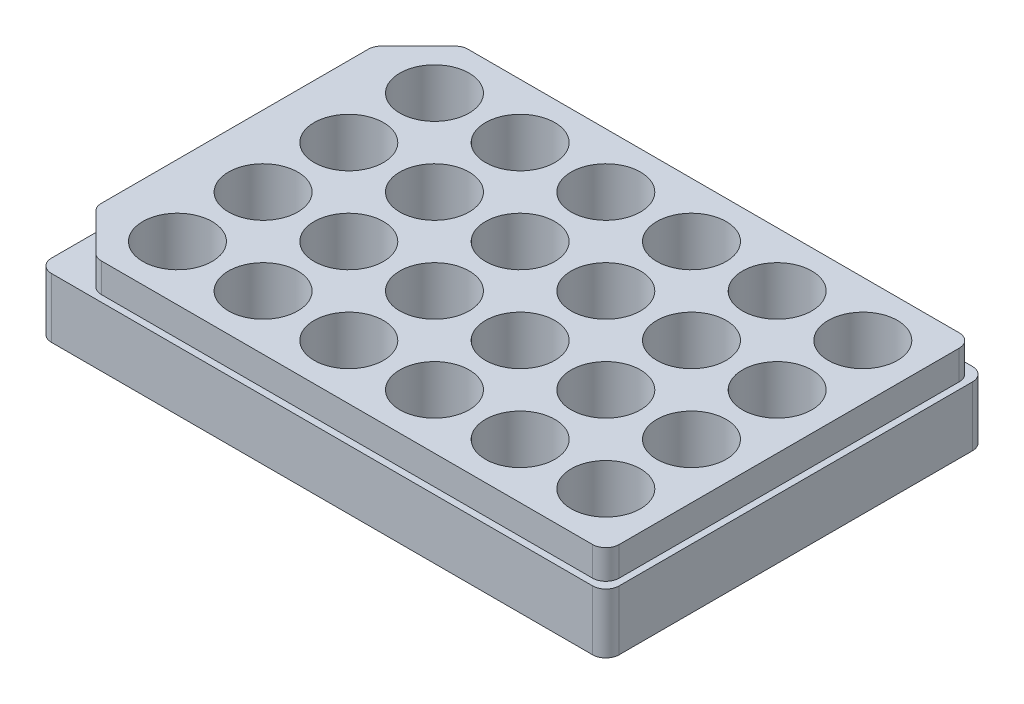
SolidWorks part; units mm, degrees
material "Acrylic (Medium-high impact)"
ref_plane "Front Plane" through (0, 0, 0) normal (0, 0, 1) x (1, 0, 0)
ref_plane "Top Plane" through (0, 0, 0) normal (0, 1, 0) x (1, 0, 0)
ref_plane "Right Plane" through (0, 0, 0) normal (1, 0, 0) x (0, 0, -1)
sketch "Sketch1" plane through (0, 0, 0) normal (0, 1, 0) x (1, 0, 0)
  line L1 (-63.945, 42.8) -> (63.945, 42.8)
  line L2 (-63.945, 42.8) -> (-63.945, -42.8)
  line L3 (-63.945, -42.8) -> (63.945, -42.8)
  line L4 (63.945, 42.8) -> (63.945, -42.8)
  line L5 (-63.945, 42.8) -> (63.945, -42.8) construction
  line L6 (-63.945, -42.8) -> (63.945, 42.8) construction
  point P0 (0, 0)
  dimension "D1" = 127.89
  dimension "D2" = 85.6
extrude "Main Plate" add sketch "Sketch1" along normal blind 20.02
sketch "Wells_LSP" plane through (0, 20.02, 0) normal (0, 1, 0) x (1, 0, 0)
  line L0 (-46.425, 28.96) -> (-27.125, 28.96) construction
  line L4 (63.945, 42.8) -> (-63.945, 42.8) construction
  line L5 (-63.945, 42.8) -> (-63.945, -42.8) construction
  circle A0 centre (-46.425, 28.96) radius 7.81
  circle A1 centre (-27.125, 28.96) radius 7.81
  circle A2 centre (-7.825, 28.96) radius 7.81
  circle A3 centre (11.475, 28.96) radius 7.81
  circle A4 centre (30.775, 28.96) radius 7.81
  circle A5 centre (50.075, 28.96) radius 7.81
  circle A6 centre (-27.125, 9.66) radius 7.81
  circle A7 centre (-7.825, 9.66) radius 7.81
  circle A8 centre (11.475, 9.66) radius 7.81
  circle A9 centre (30.775, 9.66) radius 7.81
  circle A10 centre (50.075, 9.66) radius 7.81
  circle A11 centre (-27.125, -9.64) radius 7.81
  circle A12 centre (-7.825, -9.64) radius 7.81
  circle A13 centre (11.475, -9.64) radius 7.81
  circle A14 centre (30.775, -9.64) radius 7.81
  circle A15 centre (50.075, -9.64) radius 7.81
  circle A16 centre (-27.125, -28.94) radius 7.81
  circle A17 centre (-7.825, -28.94) radius 7.81
  circle A18 centre (11.475, -28.94) radius 7.81
  circle A19 centre (30.775, -28.94) radius 7.81
  circle A20 centre (50.075, -28.94) radius 7.81
  circle A21 centre (-46.425, 9.66) radius 7.81
  circle A22 centre (-46.425, -9.64) radius 7.81
  circle A23 centre (-46.425, -28.94) radius 7.81
  dimension "D2" = 6
  dimension "D4" = 4
  dimension "D7" = 15.62
  dimension "D16" = 17.52
  dimension "D3" = 19.3
  dimension "D15" = 13.84
extrude "Wells Depth" cut sketch "Wells_LSP" against normal blind 17.14
sketch "Sketch7" plane through (0, 20.02, 0) normal (0, 1, 0) x (1, 0, 0)
  line L0 (62.445, 41.3) -> (-62.445, 41.3)
  line L1 (63.945, 42.8) -> (-63.945, 42.8)
  line L2 (63.945, 42.8) -> (63.945, -42.8)
  line L3 (63.945, -42.8) -> (-63.945, -42.8)
  line L4 (-63.945, 42.8) -> (-63.945, -42.8)
  line L5 (-62.445, 41.3) -> (-62.445, -41.3)
  line L6 (62.445, -41.3) -> (-62.445, -41.3)
  line L7 (62.445, 41.3) -> (62.445, -41.3)
  point P0 (0, 0)
  dimension "D1" = 1.5
extrude "Flange" cut sketch "Sketch7" against normal blind 6.57
sketch "Style Sketch" plane through (0, 20.02, 0) normal (0, 1, 0) x (1, 0, 0)
  line L0 (-62.445, 41.3) -> (-52.445, 41.3)
  line L1 (62.445, 41.3) -> (-62.445, 41.3) construction
  line L2 (-52.445, 41.3) -> (-62.445, 31.3)
  line L3 (-62.445, 41.3) -> (-62.445, -41.3) construction
  line L4 (-62.445, 31.3) -> (-62.445, 41.3)
  line L5 (-62.445, -41.3) -> (-52.445, -41.3)
  line L6 (-62.445, -41.3) -> (62.445, -41.3) construction
  line L7 (-62.445, -41.3) -> (-62.445, -31.3)
  line L8 (-62.445, -31.3) -> (-52.445, -41.3)
  dimension "D1" = 10
  dimension "D2" = 10
  dimension "D3" = 10
  dimension "D4" = 10
extrude "Style <3" cut sketch "Style Sketch" against normal blind 6.57
shell "Thickness Shelling" thickness 0.32
sketch "Well Elevator" plane through (0, 2.88, 0) normal (0, 1, 0) x (1, 0, 0)
  circle A0 centre (-46.425, 28.96) radius 7.81
  circle A2 centre (-27.125, 28.96) radius 7.81
  circle A3 centre (-7.825, 28.96) radius 7.81
  circle A4 centre (11.475, 28.96) radius 7.81
  circle A5 centre (30.775, 28.96) radius 7.81
  circle A6 centre (50.075, 28.96) radius 7.81
  circle A7 centre (-27.125, 9.66) radius 7.81
  circle A8 centre (-7.825, 9.66) radius 7.81
  circle A9 centre (11.475, 9.66) radius 7.81
  circle A10 centre (30.775, 9.66) radius 7.81
  circle A11 centre (50.075, 9.66) radius 7.81
  circle A12 centre (-27.125, -9.64) radius 7.81
  circle A13 centre (-7.825, -9.64) radius 7.81
  circle A14 centre (11.475, -9.64) radius 7.81
  circle A15 centre (30.775, -9.64) radius 7.81
  circle A16 centre (50.075, -9.64) radius 7.81
  circle A17 centre (-27.125, -28.94) radius 7.81
  circle A18 centre (-7.825, -28.94) radius 7.81
  circle A19 centre (11.475, -28.94) radius 7.81
  circle A20 centre (30.775, -28.94) radius 7.81
  circle A21 centre (50.075, -28.94) radius 7.81
  circle A22 centre (-46.425, 9.66) radius 7.81
  circle A23 centre (-46.425, -9.64) radius 7.81
  circle A24 centre (-46.425, -28.94) radius 7.81
  dimension "D1" = 6
  dimension "D2" = 4
extrude "Addt'l Well Elevation" add sketch "Well Elevator" along normal blind 0.95
fillet "Flange/Style Fillets" radius 3 12 edges at (-52.3125, 16.415, 40.98) (-52.3125, 16.415, -40.98) (-62.125, 16.415, -31.1675) (-52.445, 16.735, -41.3) (-62.445, 16.735, -31.3) (-62.445, 16.735, 31.3) (-62.125, 16.415, 31.1675) (-52.445, 16.735, 41.3) (62.125, 16.415, 40.98) (62.125, 16.415, -40.98) (62.445, 16.735, 41.3) (62.445, 16.735, -41.3)
fillet "Plate Edge Fillets" radius 3 8 edges at (63.945, 6.725, 42.8) (63.945, 6.725, -42.8) (-63.945, 6.725, -42.8) (-63.945, 6.725, 42.8) (63.625, 6.565, -42.48) (63.625, 6.565, 42.48) (-63.625, 6.565, -42.48) (-63.625, 6.565, 42.48)
sketch "Eq. CenterLine" [suppressed] plane through (0, 19, 0) normal (0, -1, 0) x (-1, 0, 0)
  line L0 (56.52, -2.145) -> (-56.52, -2.145) construction
  line L1 (56.52, 36.975) -> (-56.52, 36.975) construction
sketch "Sketch8" plane through (-63.625, 0, -127.25) normal (1, 0, 0) x (0, 0, -1)
  line L2 (-87.77, 0) -> (-87.77, 13.13) construction
  text T0 "(c:2014) Dionne Dawkins" font "Century Gothic" height in points 4
  dimension "D1" = 0
ref_plane "Plano1" through (-62.125, 19.7, 29.9248) normal (0, 0, 1) x (1, 0, 0)
equation "\"D1@Thickness Shelling\" = 0.32"
equation "\"D1@Addt'l Well Elevation\"=1.27 - 0.32"
